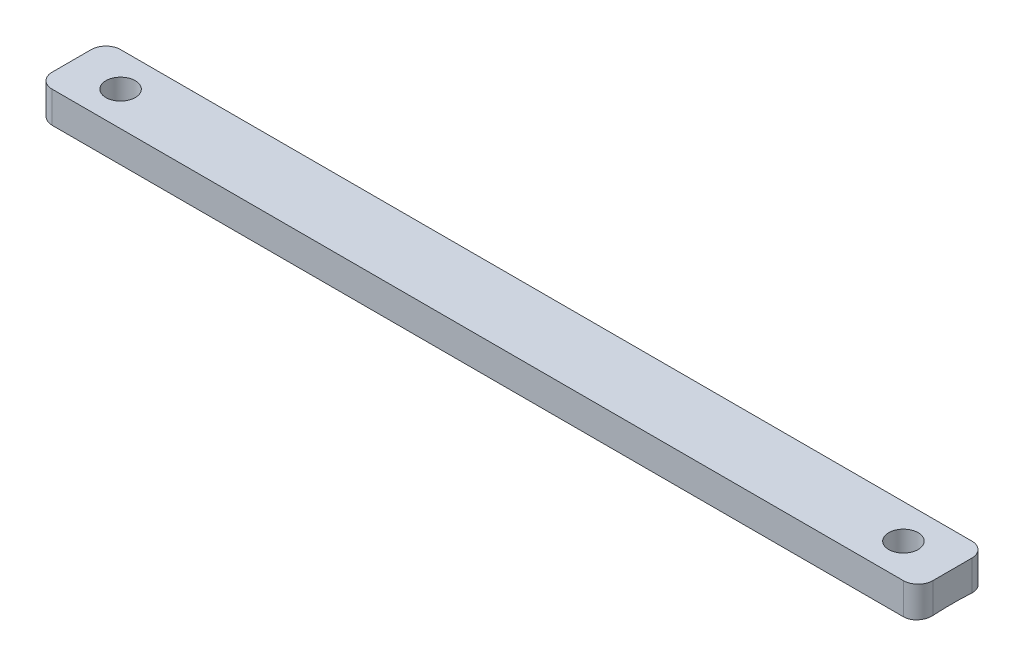
SolidWorks part; units mm, degrees
ref_plane "Front Plane" through (0, 0, 0) normal (0, 0, 1) x (1, 0, 0)
ref_plane "Top Plane" through (0, 0, 0) normal (0, 1, 0) x (1, 0, 0)
ref_plane "Right Plane" through (0, 0, 0) normal (1, 0, 0) x (0, 0, -1)
sketch "Sketch1" plane through (0, 0, 0) normal (0, 1, 0) x (1, 0, 0)
  line L1 (0, 0) -> (90, 0)
  line L2 (0, 0) -> (0, 7)
  line L3 (0, 7) -> (90, 7)
  line L4 (90, 0) -> (90, 7)
  circle A0 centre (5, 3.5) radius 1.5
  circle A1 centre (85, 3.5) radius 1.5
  point P9 (0, 0)
  point P10 (0, 0)
  point P11 (0, 3.5)
  dimension "D1" = 3
  dimension "D2" = 7
  dimension "D3" = 90
  dimension "D4" = 5
  dimension "D5" = 5
extrude "Boss-Extrude1" add sketch "Sketch1" along normal blind 3.2
sketch "Sketch2" plane through (90, 0, 0) normal (1, 0, 0) x (0, 0, -1)
  line L0 (0, 0) -> (7, 0)
  arc A0 (7, 0) -> (0, 0) centre (3.5, -36.8341) ccw
  dimension "D1" = 74
extrude "Cut-Extrude1" cut sketch "Sketch2" against normal through all both and the other way through all
fillet "Fillet1" radius 1.5 4 edges at (0, 1.6, -7) (90, 1.6, -7) (90, 1.6, 0) (0, 1.6, 0)
